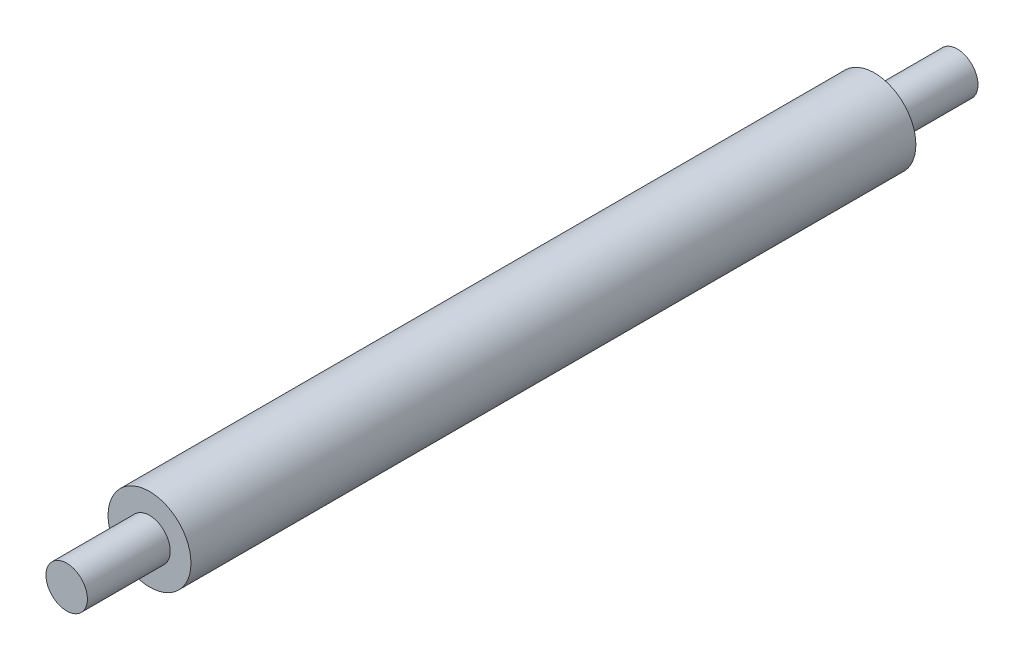
SolidWorks part; units mm, degrees
ref_plane "Front Plane" through (0, 0, 0) normal (0, 0, 1) x (1, 0, 0)
ref_plane "Top Plane" through (0, 0, 0) normal (0, 1, 0) x (1, 0, 0)
ref_plane "Right Plane" through (0, 0, 0) normal (1, 0, 0) x (0, 0, -1)
sketch "Sketch1" plane through (0, 0, 0) normal (0, 0, 1) x (1, 0, 0)
  circle A0 centre (0, 0) radius 10
  dimension "D1" = 20
extrude "Boss-Extrude1" add sketch "Sketch1" along normal mid plane 175
sketch "Sketch2" plane through (0, 0, 87.5) normal (0, 0, 1) x (1, 0, 0)
  circle A0 centre (0, 0) radius 5
  dimension "D1" = 10
extrude "Boss-Extrude2" add sketch "Sketch2" along normal blind 20
mirror "Mirror1" about plane through (0, 0, 0) normal (0, 0, 1) of "Boss-Extrude2"
